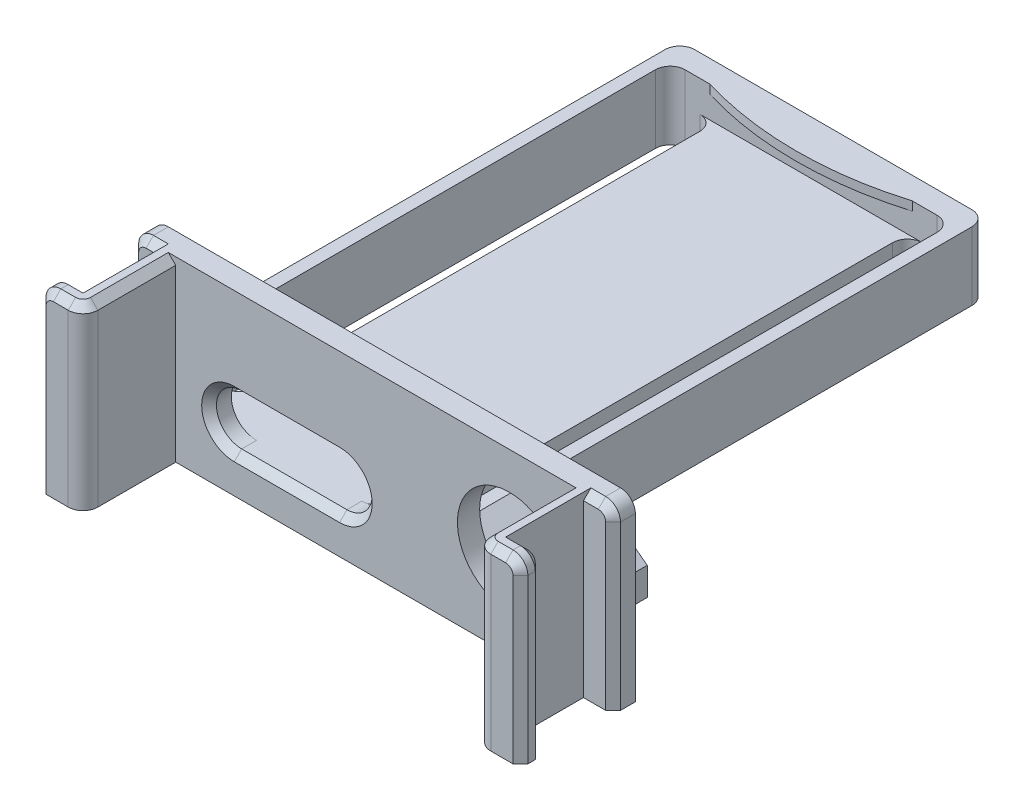
SolidWorks part; units mm, degrees
ref_plane "Front Plane" through (0, 0, 0) normal (0, 0, 1) x (1, 0, 0)
ref_plane "Top Plane" through (0, 0, 0) normal (0, 1, 0) x (1, 0, 0)
ref_plane "Right Plane" through (0, 0, 0) normal (1, 0, 0) x (0, 0, -1)
sketch "Sketch1" plane through (0, 0, 0) normal (0, 0, 1) x (1, 0, 0)
  line L1 (-14.25, 12) -> (14.25, 12)
  line L2 (-14.25, 12) -> (-14.25, 0)
  line L3 (-14.25, 0) -> (14.25, 0)
  line L4 (14.25, 12) -> (14.25, 0)
  point P4 (0, 0)
  dimension "D1" = 28.5
  dimension "D2" = 12
extrude "Boss-Extrude1" add sketch "Sketch1" against normal blind 4.75
ref_plane "Plane1" through (0, 0, -2.375) normal (0, 0, 1) x (1, 0, 0)
sketch "Sketch2" plane through (0, 0, 0) normal (0, 0, 1) x (1, 0, 0)
  line L0 (14.25, 12) -> (-14.25, 12) construction
  line L3 (-16.25, 0) -> (16.25, 0)
  line L6 (16.25, 0) -> (16.25, 14)
  line L7 (16.25, 14) -> (-16.25, 14)
  line L8 (-16.25, 14) -> (-16.25, 0)
  line L9 (16.25, 0) -> (16.25, 12)
  line L10 (16.25, 12) -> (-16.25, 12)
  line L11 (-16.25, 12) -> (-16.25, 0)
  point P0 (-16.25, 9.723)
  dimension "D1" = 2
extrude "Boss-Extrude2" add sketch "Sketch2" along normal blind 1.5
sketch "Sketch3" plane through (0, 0, -4.75) normal (0, 0, -1) x (-1, 0, 0)
  line L0 (-16.25, 0) -> (-16.25, 12) construction
  line L1 (-16.25, 12) -> (16.25, 12)
  line L2 (-16.25, 12) -> (-16.25, 0)
  line L3 (-16.25, 0) -> (16.25, 0)
  line L4 (16.25, 12) -> (16.25, 0)
  line L5 (-14.25, 12) -> (14.25, 12) construction
extrude "Boss-Extrude3" add sketch "Sketch3" along normal blind 1.5
sketch "Sketch4" plane through (0, 0, 1.5) normal (0, 0, 1) x (1, 0, 0)
  line L3 (-13.25, 0) -> (13.25, 0)
  line L6 (14.25, 0) -> (14.25, 12) construction
  line L9 (13.25, 0) -> (13.25, 12)
  line L11 (-13.25, 12) -> (-13.25, 0)
  line L15 (-13.25, 12) -> (13.25, 12)
  line L16 (16.25, 12) -> (-16.25, 12) construction
  point P0 (11.256, 2.031)
  point P2 (0, 0)
  dimension "D1" = 1
extrude "Cut-Extrude1" cut sketch "Sketch4" against normal up to surface (6.25 mm away) up to face at (15.25, 6, -4.75)
sketch "Sketch5" plane through (0, 0, -4.75) normal (0, 0, 1) x (1, 0, 0)
  line L0 (2.9706, 2.5) -> (-14.8094, 2.5) construction
  line L1 (-13.25, 12) -> (-13.25, 0) construction
  line L3 (9.25, 6) -> (13.25, 6) construction
  line L4 (13.25, 0) -> (13.25, 12) construction
  line L6 (-9.3, 5.9) -> (-2.2, 5.9)
  line L7 (-9.3, 5.9) -> (-9.3, 2.5) construction
  line L8 (-9.3, 2.5) -> (-2.2, 2.5)
  line L9 (-2.2, 5.9) -> (-2.2, 2.5) construction
  line L10 (-9.3, 5.9) -> (-2.2, 2.5) construction
  line L11 (-9.3, 2.5) -> (-2.2, 5.9) construction
  line L12 (1.75, 8.2) -> (-13.25, 8.2) construction
  line L13 (1.75, 8.2) -> (1.75, 0.2) construction
  line L14 (1.75, 0.2) -> (-13.25, 0.2) construction
  line L15 (-13.25, 8.2) -> (-13.25, 0.2) construction
  line L16 (1.75, 8.2) -> (-13.25, 0.2) construction
  line L17 (1.75, 0.2) -> (-13.25, 8.2) construction
  arc A0 (-9.3, 5.9) -> (-9.3, 2.5) centre (-9.3, 4.2) ccw
  arc A1 (-2.2, 5.9) -> (-2.2, 2.5) centre (-2.2, 4.2) cw
  circle A2 centre (9.25, 6) radius 3.5
  point P14 (-11, 4.2)
  point P15 (-0.5, 4.2)
  point P21 (9.3355, 5.25)
  point P22 (0, 0)
  point P23 (1.75, 9.128)
  point P24 (-5.75, 4.2)
  point P25 (-5.75, 4.2)
  dimension "D5" = 7
  dimension "D1" = 10.5
  dimension "D2" = 3.4
  dimension "D3" = 15
  dimension "D4" = 8
  dimension "D6" = 4
extrude "Cutouts" cut sketch "Sketch5" against normal blind 10
sketch "Sketch6" plane through (0, 0, 0) normal (0, -1, 0) x (1, 0, 0)
  line L0 (-16.25, -6.25) -> (4.45, -6.25)
  line L1 (-16.25, -6.25) -> (-16.25, -41.75)
  line L2 (-16.25, -41.75) -> (4.45, -41.75)
  line L3 (4.45, -6.25) -> (4.45, -41.75)
  line L4 (-15.4, -8.25) -> (-12.4, -8.25)
  line L5 (-15.4, -8.25) -> (-15.4, -40.25)
  line L6 (-15.4, -40.25) -> (-12.4, -40.25)
  line L7 (-12.4, -8.25) -> (-12.4, -40.25)
  line L8 (3.6, -8.25) -> (0.6, -8.25)
  line L9 (3.6, -8.25) -> (3.6, -40.25)
  line L10 (3.6, -40.25) -> (0.6, -40.25)
  line L11 (0.6, -8.25) -> (0.6, -40.25)
  line L12 (-15.4, -40.25) -> (-16.25, -40.25) construction
  line L13 (-12.4, -40.25) -> (0.6, -40.25) construction
  line L14 (3.6, -40.25) -> (4.45, -40.25) construction
  line L17 (-5.9, -40.25) -> (-5.9, -41.75) construction
  point P16 (4.1565, -40.9533)
  dimension "D1" = 3
  dimension "D2" = 2
  dimension "D3" = 19
  dimension "D4" = 34
  dimension "D5" = 0.85
  dimension "D6" = 1.5
extrude "MC Tray Boss" add sketch "Sketch6" against normal offset from surface (4.6 mm away) 0.5
sketch "Sketch7" plane through (0, 4.6, 0) normal (0, 1, 0) x (1, 0, 0)
  line L0 (3.6, 8.25) -> (3.6, 40.25) construction
  line L1 (3.6, 6.25) -> (-15.4, 6.25)
  line L2 (3.6, 6.25) -> (3.6, 40.25)
  line L3 (3.6, 40.25) -> (-15.4, 40.25)
  line L4 (-15.4, 6.25) -> (-15.4, 40.25)
  line L5 (-16.25, 6.25) -> (16.25, 6.25) construction
  point P9 (0, 0)
  point P10 (-15.4, 40.25)
extrude "MC Tray Interior Cut" cut sketch "Sketch7" against normal up to surface (2.1 mm away)
sketch "Sketch8" plane through (0, 0, -6.25) normal (0, 0, -1) x (-1, 0, 0)
  line L0 (-4.45, 4.6) -> (-4.45, 0)
  line L1 (-4.45, 0) -> (-10.5544, 0)
  line L2 (-16.25, 0) -> (-4.45, 0) construction
  line L3 (-10.5544, 0) -> (-4.45, 4.6)
  line L4 (-10.4555, 0.1223) -> (-3.2678, 5.5387) construction
  line L6 (-4.45, 4.6) -> (16.25, 4.6) construction
  point P9 (-5.3651, 3.3812)
  point P10 (0, 0)
  point P11 (-5.0376, 4.1)
  point P12 (0, 0)
  point P13 (-3.6837, 5.1)
  point P14 (-5.1829, 3.9703)
  point P15 (0, 0)
  point P16 (-4.45, 4.6)
extrude "Switch Triangle" add sketch "Sketch8" along normal offset from surface (4.5 mm away) 0.2
sketch "Sketch9" plane through (0, 0, -10.75) normal (0, 0, -1) x (-1, 0, 0)
  line L0 (-4.45, 4.6) -> (-6.9425, 4.6)
  line L1 (-6.9425, 4.6) -> (-10.5544, 1.8782)
  line L2 (-10.5544, 1.8782) -> (-10.5544, 0)
  line L4 (-10.5544, 0) -> (-4.45, 4.6) construction
  line L6 (-4.45, 4.6) -> (-4.45, 0)
  line L7 (-4.45, 0) -> (-10.5544, 0)
  line L9 (-4.45, 4.6) -> (-10.5544, 0)
  line L10 (-10.5544, 0) -> (-4.45, 0)
  line L11 (-4.45, 0) -> (-4.45, 4.6)
  line L13 (-4.45, 4.6) -> (-10.5544, 0) construction
  dimension "D1" = 1.5
  dimension "D2" = 0
extrude "Switch Tab" add sketch "Sketch9" along normal blind 2
fillet "Fillet1" radius 1 17 edges at (3.6, 1.25, -8.25) (0.6, 1.25, -8.25) (0.6, 1.25, -40.25) (-15.4, 2.3, -40.25) (3.6, 2.3, -40.25) (-12.4, 1.25, -40.25) (-12.4, 1.25, -8.25) (-15.4, 1.25, -8.25) (4.45, 2.3, -41.75) (-16.25, 2.3, -41.75) (-13.25, 6, 1.5) (-16.25, 12, 0.75) (-16.25, 12, -5.5) (16.25, 12, -5.5) (16.25, 12, 0.75) (13.25, 6, 1.5) (4.45, 2.3, -12.75)
chamfer "Chamfer1" distance 0.5 angle 45 26 edges at (13.25, 12, -2.125) (13.5429, 12, 1.2071) (14.75, 12, 1.5) (15.9571, 11.7071, 1.5) (16.25, 5.5, 1.5) (-13.25, 12, -2.125) (-13.5429, 12, 1.2071) (-14.75, 12, 1.5) (-15.9571, 11.7071, 1.5) (-16.25, 5.5, 1.5) (-14.75, 12, 0) (-15.9571, 11.7071, 0) (-16.25, 5.5, 0) (14.75, 12, 0) (15.9571, 11.7071, 0) (16.25, 5.5, 0) (14.75, 12, -4.75) (15.9571, 11.7071, -4.75) (16.25, 5.5, -4.75) (-14.75, 12, -4.75) (-15.9571, 11.7071, -4.75) (-16.25, 5.5, -4.75) (-11, 4.2, -4.75) (-5.75, 2.5, -4.75) (-5.75, 5.9, -4.75) (-0.5, 4.2, -4.75)
sketch "Sketch10" plane through (0, 4.6, 0) normal (0, 1, 0) x (1, 0, 0)
  line L0 (2.6, 40.25) -> (-14.4, 40.25) construction
  line L1 (-12.7269, 40.25) -> (-5.9, 40.25)
  line L2 (-5.9, 40.25) -> (0.9269, 40.25)
  line L3 (-5.9, 40.25) -> (-5.9, 39.25) construction
  arc A0 (-12.7269, 40.25) -> (0.9269, 40.25) centre (-5.9, 63.0535) ccw
  dimension "D1" = 1
extrude "Boss-Extrude7" add sketch "Sketch10" against normal blind 0.6
